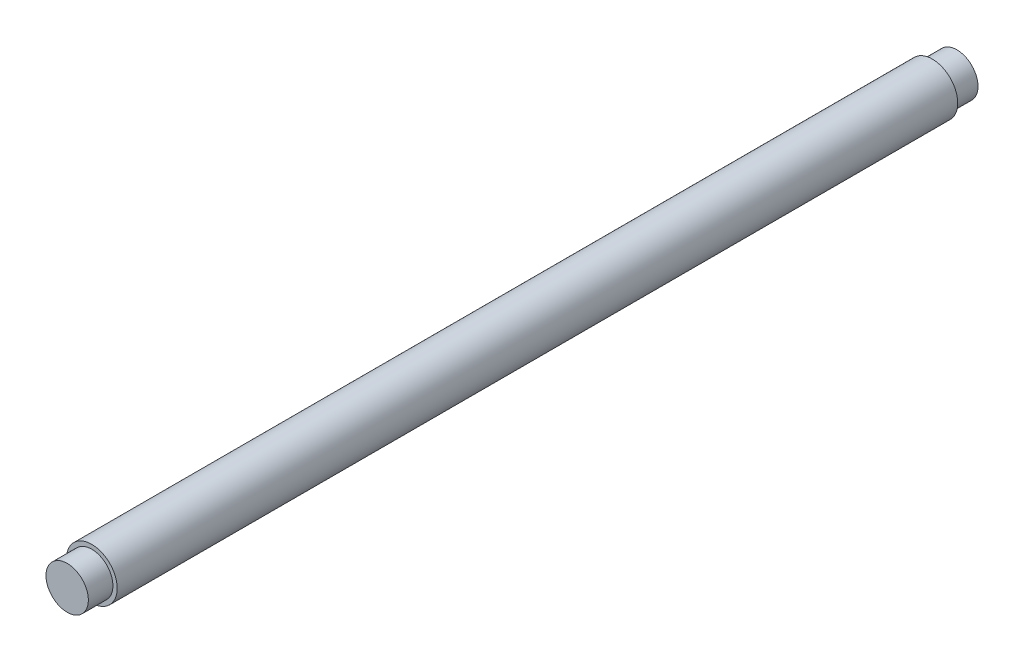
SolidWorks part; units mm, degrees
ref_plane "正面" through (0, 0, 0) normal (0, 0, 1) x (1, 0, 0)
ref_plane "平面" through (0, 0, 0) normal (0, 1, 0) x (1, 0, 0)
ref_plane "右側面" through (0, 0, 0) normal (1, 0, 0) x (0, 0, -1)
sketch "ｽｹｯﾁ1" plane through (0, 0, 0) normal (0, 0, 1) x (1, 0, 0)
  circle A0 centre (0, 0) radius 6
  dimension "D1" = 12
extrude "ﾎﾞｽ - 押し出し1" add sketch "ｽｹｯﾁ1" along normal mid plane 210
sketch "ｽｹｯﾁ2" plane through (0, 0, -105) normal (0, 0, -1) x (-1, 0, 0)
  circle A0 centre (0, 0) radius 6
  circle A1 centre (0, 0) radius 5
  dimension "D1" = 10
extrude "ｶｯﾄ - 押し出し1" cut sketch "ｽｹｯﾁ2" against normal blind 5.8
mirror "ﾐﾗｰ1" about plane through (0, 0, 0) normal (0, 0, 1) of "ｶｯﾄ - 押し出し1"
